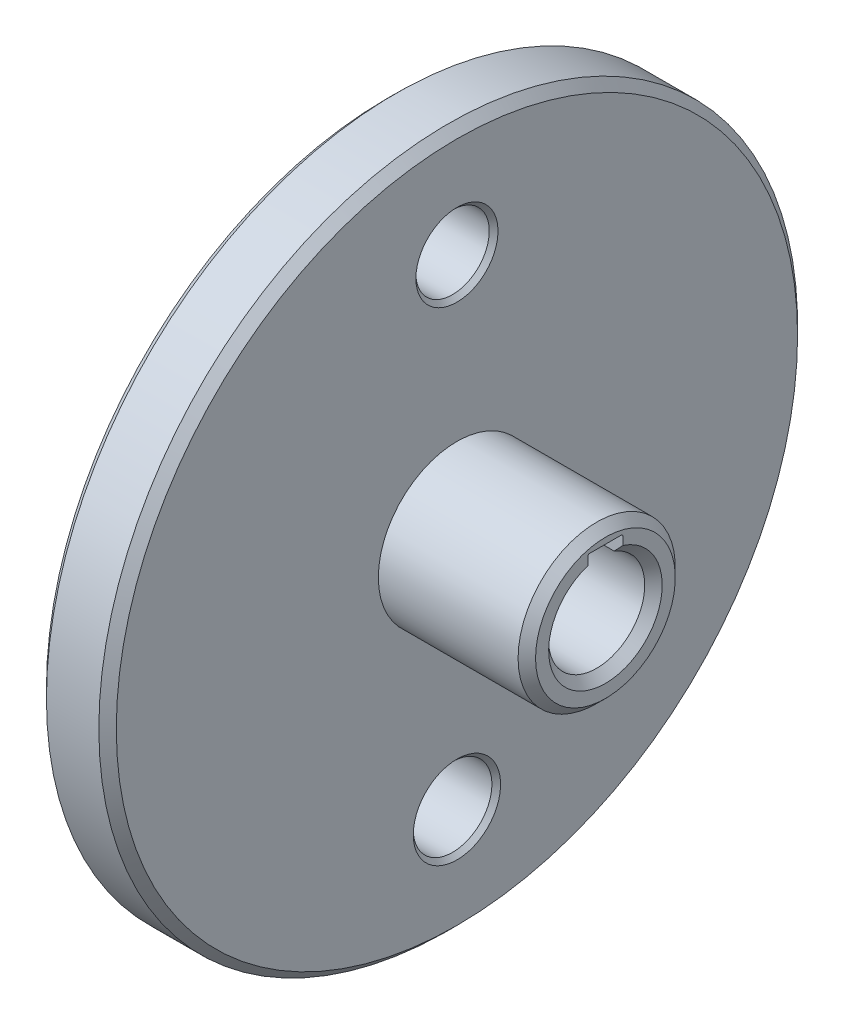
SolidWorks part; units mm, degrees
ref_plane "Спереди" through (0, 0, 0) normal (0, 0, 1) x (1, 0, 0)
ref_plane "Сверху" through (0, 0, 0) normal (0, 1, 0) x (1, 0, 0)
ref_plane "Справа" through (0, 0, 0) normal (1, 0, 0) x (0, 0, -1)
sketch "Эскиз1" plane through (0, 0, 0) normal (0, 0, 1) x (1, 0, 0)
  line L0 (0, 0) -> (33.6907, 0) construction
  line L1 (0, 12.5) -> (0, 40)
  line L2 (0, 40) -> (8, 40)
  line L3 (8, 40) -> (8, 9)
  line L4 (8, 9) -> (25, 9)
  line L5 (25, 9) -> (25, 5.5)
  line L6 (25, 5.5) -> (2, 5.5)
  line L7 (2, 5.5) -> (2, 12.5)
  line L8 (2, 12.5) -> (0, 12.5)
  dimension "dH7" = 11
  dimension "d1" = 18
  dimension "d2" = 25
  dimension "D" = 80
  dimension "l" = 25
  dimension "l1" = 8
  dimension "l2" = 2
revolve "Повернуть1" add sketch "Эскиз1" angle 360 about L0
sketch "Эскиз2" plane through (0, 0, 0) normal (1, 0, 0) x (0, 0, -1)
  line L0 (0, 0) -> (35.7156, 0) construction
  line L1 (0, 27.5) -> (0, 0) construction
  circle A1 centre (0, 27.5) radius 4.2
  dimension "d3" = 8.4
  dimension "D1/2" = 27.5
  dimension "a3" = 90
extrude "Вырез-Вытянуть1" cut sketch "Эскиз2" along normal through all
sketch "Эскиз3" plane through (0, 0, 0) normal (1, 0, 0) x (0, 0, -1)
  line L0 (0, 0) -> (-36.0957, 0) construction
  line L1 (0, 0) -> (0, -27.5) construction
  circle A1 centre (0, -27.5) radius 4.5
  dimension "d4" = 9
  dimension "D1/2" = 27.5
  dimension "a4" = 90
extrude "Вырез-Вытянуть2" cut sketch "Эскиз3" along normal through all
sketch "Эскиз5" plane through (0, 0, 0) normal (1, 0, 0) x (0, 0, -1)
  line L1 (2, 7.3) -> (-2, 7.3)
  line L2 (2, 7.3) -> (2, 3.3)
  line L3 (2, 3.3) -> (-2, 3.3)
  line L4 (-2, 7.3) -> (-2, 3.3)
  circle A0 centre (0, 0) radius 5.5 construction
  point P4 (0, 7.3)
  point P6 (0, -5.5)
  dimension "B" = 4
  dimension "h" = 12.8
extrude "Вырез-Вытянуть3" cut sketch "Эскиз5" along normal through all
fillet "Скругление1" radius 0.2 2 edges at (13.5, 7.3, -2) (13.5, 7.3, 2)
chamfer "Фаска1" distance 1 angle 45 4 edges at (8, 0, 40) (0, 0, 40) (25, -5.5, 0) (25, 0, 9)
chamfer "Фаска2" distance 0.5 angle 45 2 edges at (8, -27.5, 4.5) (8, 27.5, 4.2)
pattern_circular "Круговой массив1" [suppressed] count 2 every 120
pattern_circular "Круговой массив2" [suppressed] count 2 every 90
